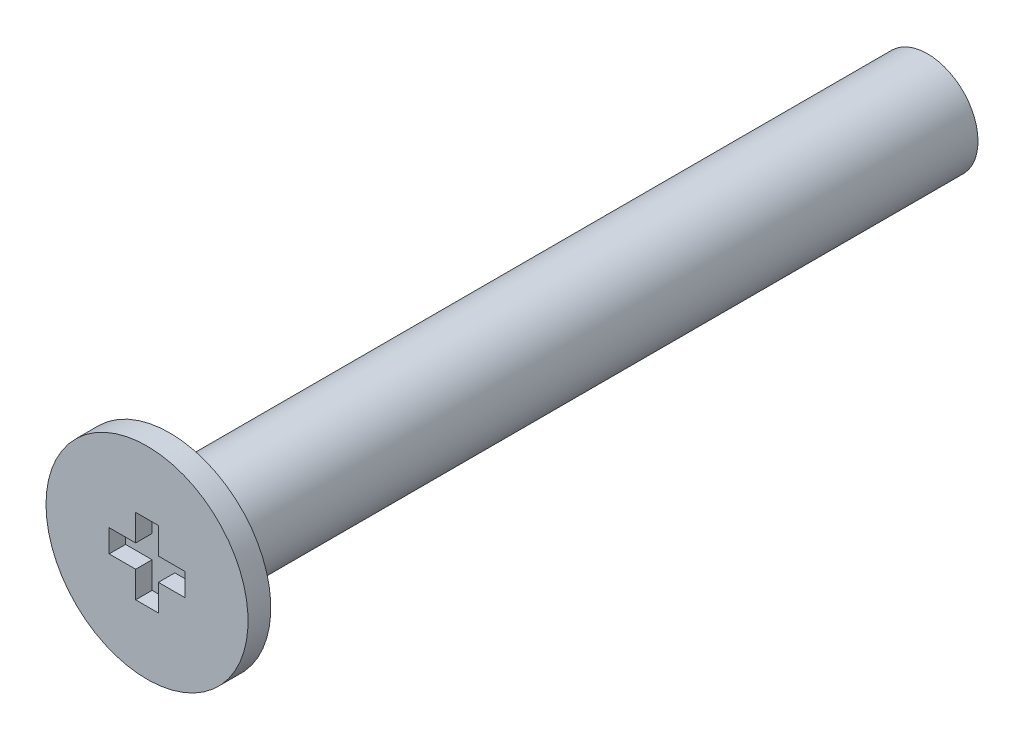
SolidWorks part; units mm, degrees
ref_plane "前视基准面" through (0, 0, 0) normal (0, 0, 1) x (1, 0, 0)
ref_plane "上视基准面" through (0, 0, 0) normal (0, 1, 0) x (1, 0, 0)
ref_plane "右视基准面" through (0, 0, 0) normal (1, 0, 0) x (0, 0, -1)
other "Configuration Table"
sketch "草图1" plane through (0, 0, 0) normal (0, 0, 1) x (1, 0, 0)
  circle A0 centre (0, 0) radius 2
extrude "标准杆径_头下长度" add sketch "草图1" against normal blind 30
sketch "草图2" plane through (0, 0, 0) normal (0, 0, 1) x (1, 0, 0)
  circle A0 centre (0, 0) radius 3.5
sketch "草图4" plane through (0, 0, 0) normal (0, 1, 0) x (1, 0, 0)
  line L0 (0, 0) -> (4.7, 0)
  line L1 (4.7, 0) -> (4.7, -0.2884)
  line L2 (0, -2.5) -> (0, 0)
  line L3 (0, 2) -> (0, -4.5) construction
  arc A0 (4.7, -0.2884) -> (0, -2.5) centre (0, 3.6) cw
sketch "草图5" plane through (0, 0, 0) normal (0, 0, 1) x (1, 0, 0)
  line L0 (-0.5, -2.15) -> (0.5, -2.15)
  line L1 (0.5, -2.15) -> (0.5, -0.5)
  line L2 (0.5, -0.5) -> (2.15, -0.5)
  line L3 (2.15, -0.5) -> (2.15, 0.5)
  line L4 (2.15, 0.5) -> (0.5, 0.5)
  line L5 (0.5, 0.5) -> (0.5, 2.15)
  line L6 (0.5, 2.15) -> (-0.5, 2.15)
  line L7 (-0.5, 2.15) -> (-0.5, 0.5)
  line L8 (-0.5, 0.5) -> (-2.15, 0.5)
  line L9 (-2.15, 0.5) -> (-2.15, -0.5)
  line L10 (-2.15, -0.5) -> (-0.5, -0.5)
  line L11 (-0.5, -0.5) -> (-0.5, -2.15)
sketch "草图6" plane through (0, 0, 0) normal (0, 1, 0) x (1, 0, 0)
  line L0 (0, 0) -> (4, 0)
  line L1 (4, 0) -> (4, -0.9)
  line L2 (4, -0.9) -> (0, -0.9)
  line L3 (0, -0.9) -> (0, 0)
  line L4 (0, 2) -> (0, -2.9) construction
revolve "已确认_十字槽超薄头" add sketch "草图6" angle 360 about L4
sketch "草图7" plane through (0, 0, 0) normal (0, 0, 1) x (1, 0, 0)
  line L0 (-0.45, -1.5) -> (0.45, -1.5)
  line L1 (0.45, -1.5) -> (0.45, -0.45)
  line L2 (0.45, -0.45) -> (1.5, -0.45)
  line L3 (1.5, -0.45) -> (1.5, 0.45)
  line L4 (1.5, 0.45) -> (0.45, 0.45)
  line L5 (0.45, 0.45) -> (0.45, 1.5)
  line L6 (0.45, 1.5) -> (-0.45, 1.5)
  line L7 (-0.45, 1.5) -> (-0.45, 0.45)
  line L8 (-0.45, 0.45) -> (-1.5, 0.45)
  line L9 (-1.5, 0.45) -> (-1.5, -0.45)
  line L10 (-1.5, -0.45) -> (-0.45, -0.45)
  line L11 (-0.45, -0.45) -> (-0.45, -1.5)
extrude "十字槽_PH2_简化" cut sketch "草图7" against normal blind 0.66 from offset 0.91
